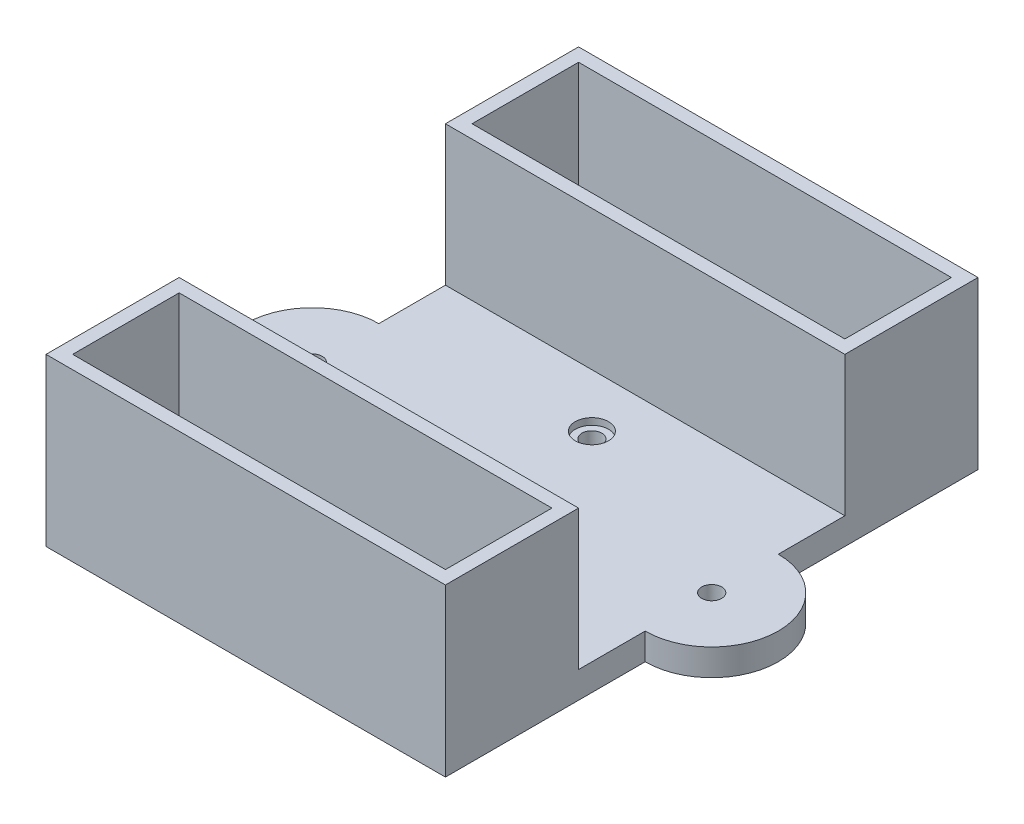
SolidWorks part; units mm, degrees
ref_plane "Front Plane" through (0, 0, 0) normal (0, 0, 1) x (1, 0, 0)
ref_plane "Top Plane" through (0, 0, 0) normal (0, 1, 0) x (1, 0, 0)
ref_plane "Right Plane" through (0, 0, 0) normal (1, 0, 0) x (0, 0, -1)
sketch "Sketch1" plane through (0, 0, 0) normal (0, 1, 0) x (1, 0, 0)
  line L0 (-30, 0) -> (30, 0) construction
  line L1 (-30, -40) -> (30, -40)
  line L2 (-30, -40) -> (-30, -10)
  line L3 (-30, 40) -> (30, 40)
  line L4 (30, -40) -> (30, -10)
  line L5 (-30, -40) -> (30, 40) construction
  line L6 (-30, 40) -> (30, -40) construction
  line L7 (0, 40) -> (0, -40) construction
  line L8 (-30, 10) -> (-30, 40)
  line L9 (30, 10) -> (30, 40)
  line L10 (-21.5, 30) -> (21.5, 30) construction
  line L11 (-18, -22) -> (-18, -38)
  line L12 (-18, 22) -> (18, 22)
  line L13 (-18, 22) -> (-18, 38)
  line L14 (-18, 38) -> (18, 38)
  line L15 (18, 22) -> (18, 38)
  line L16 (-18, 22) -> (18, 38) construction
  line L17 (-18, 38) -> (18, 22) construction
  line L18 (-18, -22) -> (18, -22)
  line L19 (18, -22) -> (18, -38)
  line L20 (-18, -38) -> (18, -38)
  line L21 (-18, -22) -> (18, -38) construction
  line L22 (-18, -38) -> (18, -22) construction
  line L23 (-21.5, -30) -> (21.5, -30) construction
  circle A0 centre (30, 0) radius 1.5
  arc A1 (-30, 10) -> (-30, -10) centre (-30, 0) ccw
  circle A2 centre (-30, 0) radius 1.5
  arc A3 (30, 10) -> (30, -10) centre (30, 0) cw
  circle A4 centre (0, 12) radius 1.5
  circle A5 centre (0, -12) radius 1.5
  circle A6 centre (-21.5, 30) radius 1
  circle A7 centre (21.5, 30) radius 1
  circle A8 centre (21.5, -30) radius 1
  circle A9 centre (-21.5, -30) radius 1
  point P0 (0, 0)
  point P28 (0, 30)
  point P37 (0, -30)
  dimension "D1" = 80
  dimension "D3" = 10
  dimension "D4" = 3
  dimension "D5" = 3
  dimension "D7" = 2
  dimension "D2" = 60
  dimension "D6" = 12
  dimension "D8" = 10
  dimension "D9" = 8.5
  dimension "D10" = 36
  dimension "D11" = 16
extrude "Boss-Extrude1" add sketch "Sketch1" along normal blind 4
sketch "Sketch3" plane through (0, 4, 0) normal (0, 1, 0) x (1, 0, 0)
  line L0 (-18, -38) -> (18, -22) construction
  line L1 (-30, 20) -> (30, 20)
  line L2 (-30, 20) -> (-30, 40)
  line L3 (-30, 40) -> (30, 40)
  line L4 (30, 20) -> (30, 40)
  line L5 (-30, 20) -> (30, 40) construction
  line L6 (-30, 40) -> (30, 20) construction
  line L7 (-30, -20) -> (30, -20)
  line L8 (-30, -20) -> (-30, -40)
  line L9 (-30, -40) -> (30, -40)
  line L10 (30, -20) -> (30, -40)
  line L11 (-30, -20) -> (30, -40) construction
  line L12 (-30, -40) -> (30, -20) construction
  line L13 (-18, 22) -> (18, 38) construction
  line L14 (-28, 22) -> (28, 22)
  line L15 (-28, 22) -> (-28, 38)
  line L16 (-28, 38) -> (28, 38)
  line L17 (28, 22) -> (28, 38)
  line L18 (-28, 22) -> (28, 38) construction
  line L19 (-28, 38) -> (28, 22) construction
  line L20 (-18, -22) -> (18, -38) construction
  line L21 (-28, -38) -> (28, -38)
  line L22 (-28, -38) -> (-28, -22)
  line L23 (-28, -22) -> (28, -22)
  line L24 (28, -38) -> (28, -22)
  line L25 (-28, -38) -> (28, -22) construction
  line L26 (-28, -22) -> (28, -38) construction
  point P0 (0, 30)
  point P7 (0, -30)
  point P15 (0, 30)
  point P22 (0, -30)
  dimension "D1" = 2
  dimension "D2" = 2
  dimension "D3" = 2
  dimension "D4" = 2
extrude "Boss-Extrude2" add sketch "Sketch3" along normal blind 21
sketch "Sketch4" plane through (0, 4, 0) normal (0, 1, 0) x (1, 0, 0)
  line L0 (-10.0008, 0) -> (9.7221, 0) construction
  line L1 (-30, 0) -> (30, 0) construction
  circle A0 centre (0, 12) radius 2.5
  circle A1 centre (0, -12) radius 2.5
  dimension "D1" = 5
extrude "Cut-Extrude1" cut sketch "Sketch4" against normal blind 1
sketch "Sketch5" plane through (0, 25, 0) normal (0, 1, 0) x (1, 0, 0)
  line L1 (-28, 38) -> (28, 38)
  line L2 (-28, 38) -> (-28, 22)
  line L3 (-28, 22) -> (28, 22)
  line L4 (28, 38) -> (28, 22)
extrude "Cut-Extrude2" cut sketch "Sketch5" against normal blind 23
mirror "Mirror1" about plane through (0, 0, 0) normal (0, 0, 1) of "Cut-Extrude2"
